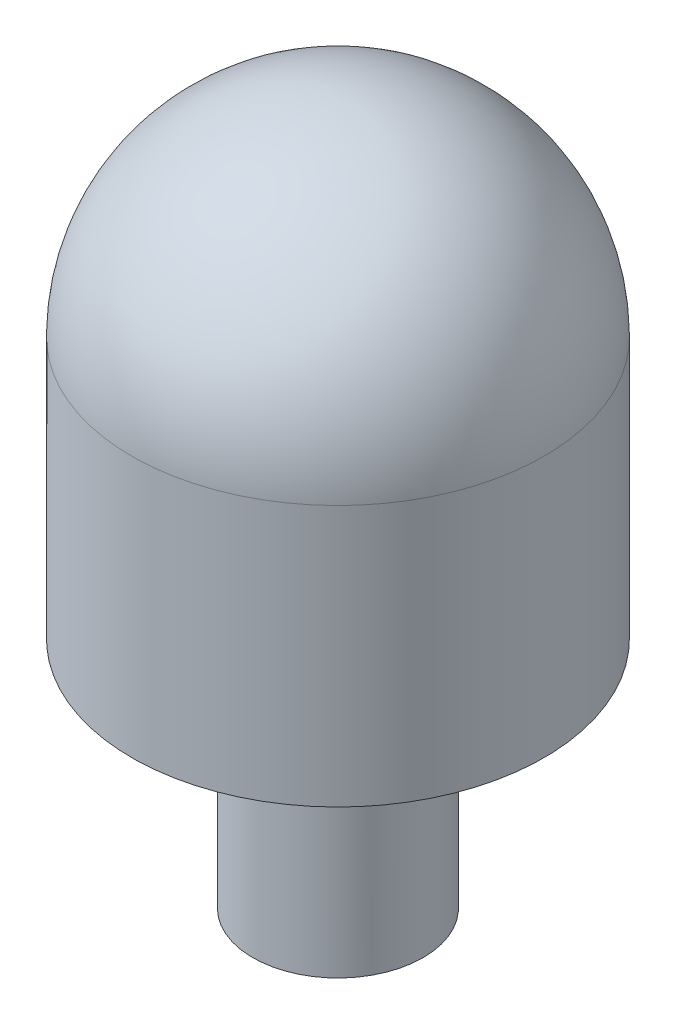
SolidWorks part; units mm, degrees
ref_plane "Front Plane" through (0, 0, 0) normal (0, 0, 1) x (1, 0, 0)
ref_plane "Top Plane" through (0, 0, 0) normal (0, 1, 0) x (1, 0, 0)
ref_plane "Right Plane" through (0, 0, 0) normal (1, 0, 0) x (0, 0, -1)
sketch "Sketch1" plane through (0, 0, 0) normal (0, 0, 1) x (1, 0, 0)
  line L0 (0, 0) -> (-7.5, 0)
  line L1 (-7.5, 0) -> (-7.5, 9.5)
  line L2 (0, 17) -> (0, 0)
  arc A0 (-7.5, 9.5) -> (0, 17) centre (0, 9.5) cw
  point P6 (-0.0728, 17.8345)
  point P7 (0, 0)
  dimension "D1" = 7.5
  dimension "D2" = 9.5
revolve "Revolve1" add sketch "Sketch1" angle 360 about L2
sketch "Sketch2" plane through (0, 0, 0) normal (0, -1, 0) x (1, 0, 0)
  line L0 (-2.1362, 3.7) -> (-4.2724, 0)
  line L1 (2.0207, -3.5) -> (4.0415, 0) construction
  line L2 (4.0415, 0) -> (2.0207, 3.5) construction
  line L3 (2.0207, 3.5) -> (-2.0207, 3.5) construction
  line L4 (-2.0207, 3.5) -> (-4.0415, 0) construction
  line L5 (-4.0415, 0) -> (-2.0207, -3.5) construction
  line L6 (-2.0207, -3.5) -> (2.0207, -3.5) construction
  line L7 (-4.2724, 0) -> (-2.1362, -3.7)
  line L8 (-2.1362, -3.7) -> (2.1362, -3.7)
  line L9 (2.1362, -3.7) -> (4.2724, 0)
  line L10 (4.2724, 0) -> (2.1362, 3.7)
  line L11 (2.1362, 3.7) -> (-2.1362, 3.7)
  circle A0 centre (0, 0) radius 3.5 construction
  dimension "D1" = 7
  dimension "D2" = 0.2
extrude "Cut-Extrude1" cut sketch "Sketch2" against normal blind 3.2 from offset 3 offset against normal yes
sketch "Sketch3" plane through (0, 0, 0) normal (0, -1, 0) x (1, 0, 0)
  circle A0 centre (0, 0) radius 2.1
  dimension "D1" = 4.2
extrude "Cut-Extrude2" cut sketch "Sketch3" against normal up to next
sketch "Sketch4" plane through (0, 0, 0) normal (0, -1, 0) x (1, 0, 0)
  circle A0 centre (0, 0) radius 2.6
  circle A1 centre (0, 0) radius 3.1
  circle A2 centre (0, 0) radius 2.1 construction
  point P5 (0, 0)
  point P7 (0, 0)
  dimension "D1" = 0.5
  dimension "D2" = 0.5
extrude "Boss-Extrude1" add sketch "Sketch4" along normal blind 8 from offset 0.5
sketch "Sketch5" plane through (0, 0, 0) normal (0, -1, 0) x (1, 0, 0)
  line L0 (-0.25, 3.0899) -> (-0.2097, 2.5915)
  line L2 (0, 3.1) -> (0, 0) construction
  line L3 (0.2097, 2.5915) -> (0.25, 3.0899)
  line L5 (-0.2097, 2.5915) -> (0, 0) construction
  line L6 (0, 0) -> (0.2097, 2.5915) construction
  line L7 (2.5915, -0.2097) -> (3.0899, -0.25)
  line L8 (3.0899, 0.25) -> (2.5915, 0.2097)
  line L9 (-0.2097, -2.5915) -> (-0.25, -3.0899)
  line L10 (0.25, -3.0899) -> (0.2097, -2.5915)
  line L11 (-2.5915, 0.2097) -> (-3.0899, 0.25)
  line L12 (-3.0899, -0.25) -> (-2.5915, -0.2097)
  circle A0 centre (0, 0) radius 2.6 construction
  arc A1 (3.0899, -0.25) -> (3.0899, 0.25) centre (0, 0) ccw
  circle A4 centre (0, 0) radius 3.1 construction
  arc A5 (0.25, 3.0899) -> (-0.25, 3.0899) centre (0, 0) ccw
  arc A6 (0.2097, 2.5915) -> (-0.2097, 2.5915) centre (0, 0) ccw
  arc A7 (2.5915, -0.2097) -> (2.5915, 0.2097) centre (0, 0) ccw
  arc A8 (-0.25, -3.0899) -> (0.25, -3.0899) centre (0, 0) ccw
  arc A9 (-0.2097, -2.5915) -> (0.2097, -2.5915) centre (0, 0) ccw
  arc A10 (-3.0899, 0.25) -> (-3.0899, -0.25) centre (0, 0) ccw
  arc A11 (-2.5915, 0.2097) -> (-2.5915, -0.2097) centre (0, 0) ccw
  point P8 (0, 0)
  point P11 (0, 0)
  point P26 (0, 0)
  dimension "D2" = 0.5
  dimension "D3" = 0.25
  dimension "D1" = 4
extrude "Boss-Extrude2" add sketch "Sketch5" along normal up to next
